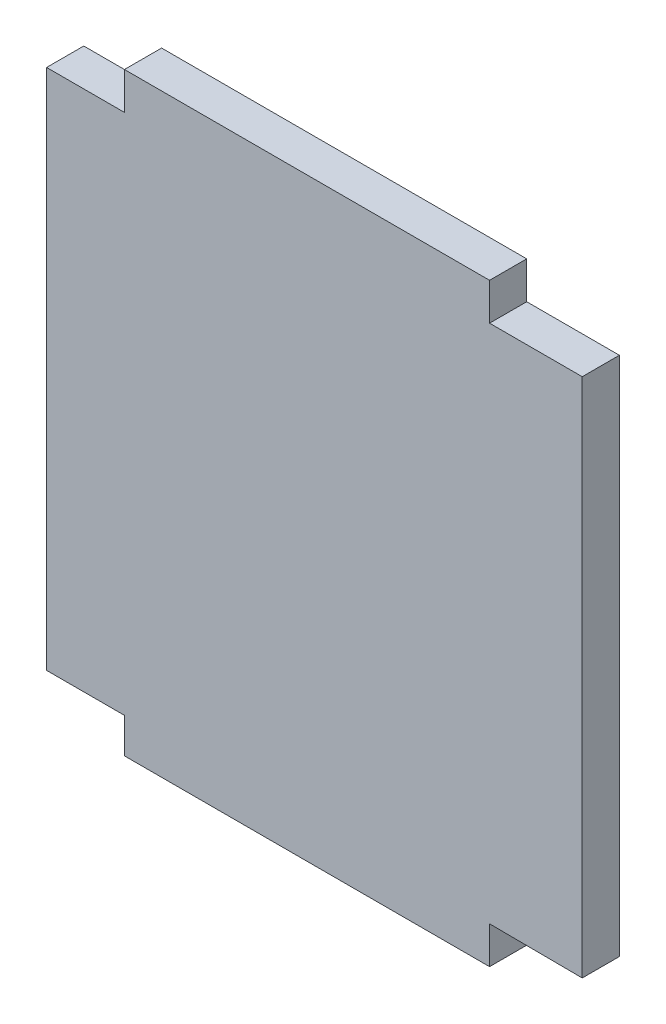
SolidWorks part; units mm, degrees
ref_plane "Front Plane" through (0, 0, 0) normal (0, 0, 1) x (1, 0, 0)
ref_plane "Top Plane" through (0, 0, 0) normal (0, 1, 0) x (1, 0, 0)
ref_plane "Right Plane" through (0, 0, 0) normal (1, 0, 0) x (0, 0, -1)
sketch "Sketch1" plane through (0, 0, 0) normal (0, 0, 1) x (1, 0, 0)
  line L0 (-60.7833, 39.7117) -> (-60.7833, 44.5113)
  line L3 (-71.4262, 44.5113) -> (-71.4262, 115.9117)
  line L4 (-60.7833, 115.9117) -> (-71.4262, 115.9117)
  line L5 (-60.7833, 115.9117) -> (-60.7833, 120.9917)
  line L7 (-60.7833, 120.9917) -> (-10.8594, 120.9917)
  line L8 (-10.8594, 120.9917) -> (-10.8594, 115.9117)
  line L9 (-10.8594, 115.9117) -> (1.8138, 115.9117)
  line L10 (1.8138, 115.9117) -> (1.8138, 44.7079)
  line L11 (1.8138, 44.7079) -> (-10.8594, 44.7917)
  line L12 (-10.8594, 44.7917) -> (-10.8594, 39.7117)
  line L14 (-10.8594, 39.7117) -> (-60.7833, 39.7117)
  line L15 (-71.4262, 44.5113) -> (-60.7833, 44.5113)
extrude "Boss-Extrude1" add sketch "Sketch1" along normal blind 5.08 contours L5 L7 L8 L9 L10 L11 L12 L14 L0 L15 L3 L4
